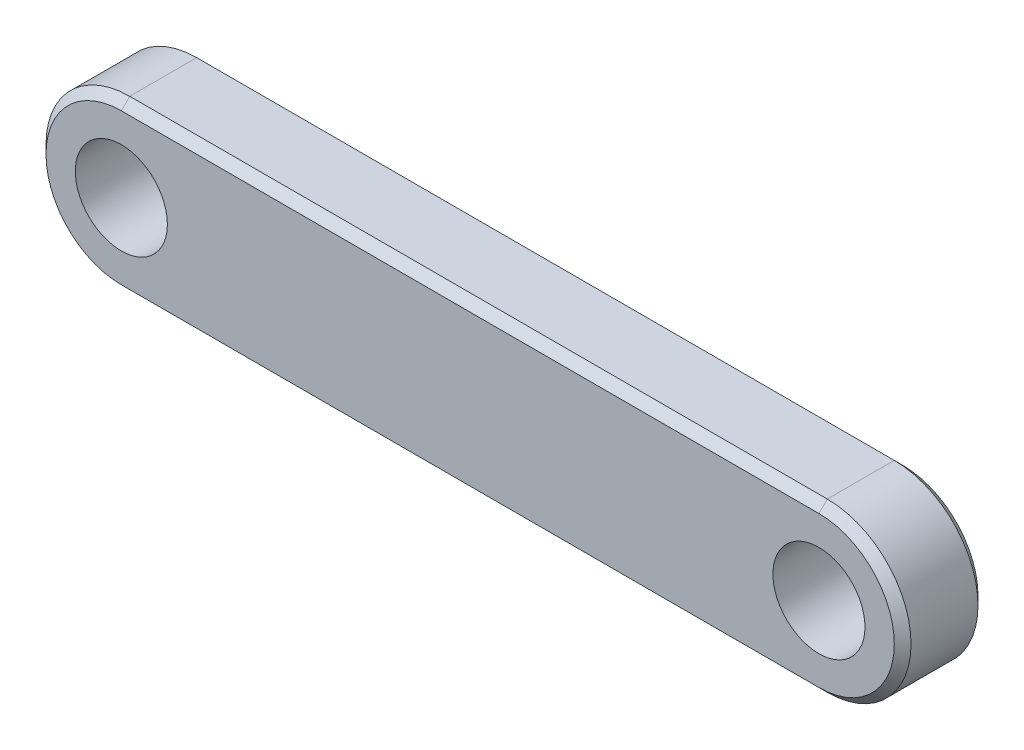
SolidWorks part; units mm, degrees
ref_plane "前视基准面" through (0, 0, 0) normal (0, 0, 1) x (1, 0, 0)
ref_plane "上视基准面" through (0, 0, 0) normal (0, 1, 0) x (1, 0, 0)
ref_plane "右视基准面" through (0, 0, 0) normal (1, 0, 0) x (0, 0, -1)
sketch "草图1" plane through (0, 0, 0) normal (0, 0, 1) x (1, 0, 0)
  line L0 (-12.5, 0) -> (12.5, 0) construction
  line L1 (-12.5, 3) -> (12.5, 3)
  line L2 (-12.5, -3) -> (12.5, -3)
  arc A0 (-12.5, 3) -> (-12.5, -3) centre (-12.5, 0) ccw
  arc A1 (12.5, -3) -> (12.5, 3) centre (12.5, 0) ccw
  circle A2 centre (-12.5, 0) radius 1.65
  circle A3 centre (12.5, 0) radius 1.65
  point P2 (0, 0)
  dimension "D1" = 3
  dimension "D3" = 3.3
  dimension "D2" = 25
extrude "凸台-拉伸1" add sketch "草图1" along normal blind 3
chamfer "倒角1" distance 0.3 angle 45 10 edges at (14.15, 0, 0) (-10.85, 0, 0) (0, -3, 3) (15.5, 0, 3) (-15.5, 0, 3) (0, 3, 3) (0, -3, 0) (15.5, 0, 0) (-15.5, 0, 0) (0, 3, 0)
